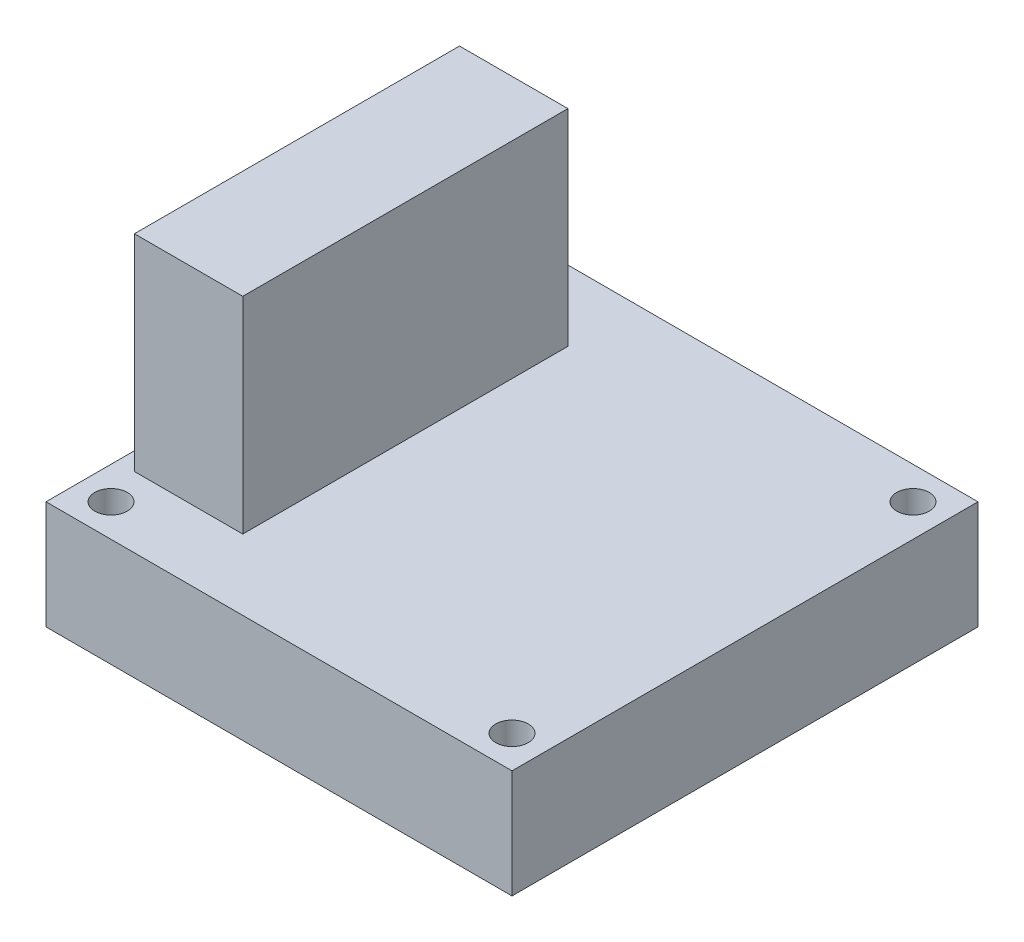
SolidWorks part; units mm, degrees
ref_plane "前基準面" through (0, 0, 0) normal (0, 0, 1) x (1, 0, 0)
ref_plane "上基準面" through (0, 0, 0) normal (0, 1, 0) x (1, 0, 0)
ref_plane "右基準面" through (0, 0, 0) normal (1, 0, 0) x (0, 0, -1)
sketch "草圖1" plane through (0, 0, 0) normal (0, 1, 0) x (1, 0, 0)
  line L1 (-21.5, -21.5) -> (21.5, -21.5)
  line L2 (-21.5, -21.5) -> (-21.5, 21.5)
  line L3 (-21.5, 21.5) -> (21.5, 21.5)
  line L4 (21.5, -21.5) -> (21.5, 21.5)
  line L5 (-21.5, -21.5) -> (21.5, 21.5) construction
  line L6 (-21.5, 21.5) -> (21.5, -21.5) construction
  circle A0 centre (-18.5, 18.5) radius 1.5
  circle A1 centre (18.5, 18.5) radius 1.5
  circle A2 centre (18.5, -18.5) radius 1.5
  circle A3 centre (-18.5, -18.5) radius 1.5
  point P0 (0, 0)
  point P11 (0, 0)
  point P14 (0, 0)
  point P17 (0, 0)
  point P20 (0, 0)
  dimension "D2" = 3
  dimension "D1" = 43
  dimension "D3" = 3
  dimension "D4" = 4
extrude "填料-伸長1" add sketch "草圖1" along normal blind 10
sketch "草圖2" plane through (0, 10, 0) normal (0, 1, 0) x (1, 0, 0)
  line L1 (-9.8419, -15) -> (-19.8419, -15)
  line L2 (-9.8419, -15) -> (-9.8419, 15)
  line L3 (-9.8419, 15) -> (-19.8419, 15)
  line L4 (-19.8419, -15) -> (-19.8419, 15)
  line L5 (-9.8419, -15) -> (-19.8419, 15) construction
  line L6 (-9.8419, 15) -> (-19.8419, -15) construction
  point P0 (-14.8419, 0)
  point P7 (-16.5, 0)
  point P8 (0, 0)
  dimension "D1" = 30
  dimension "D2" = 10
extrude "填料-伸長2" add sketch "草圖2" along normal blind 19
